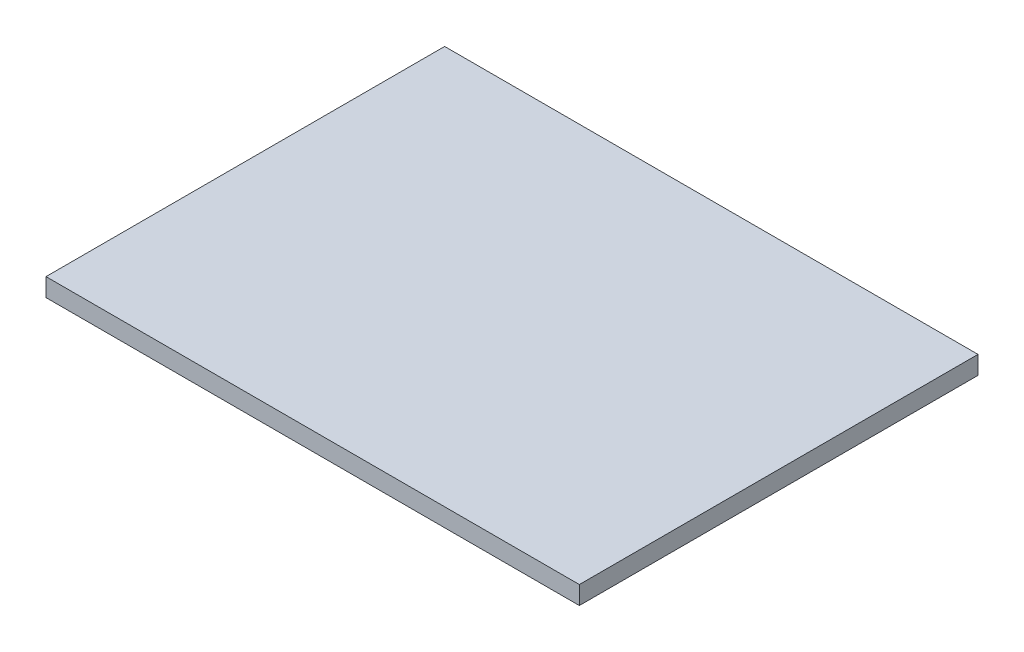
SolidWorks part; units mm, degrees
ref_plane "Płaszczyzna przednia" through (0, 0, 0) normal (0, 0, 1) x (1, 0, 0)
ref_plane "Płaszczyzna górna" through (0, 0, 0) normal (0, 1, 0) x (1, 0, 0)
ref_plane "Płaszczyzna prawa" through (0, 0, 0) normal (1, 0, 0) x (0, 0, -1)
sketch "Szkic1" plane through (0, 0, 0) normal (0, 1, 0) x (1, 0, 0)
  line L1 (-146.5, -109.5) -> (146.5, -109.5)
  line L2 (-146.5, -109.5) -> (-146.5, 109.5)
  line L3 (-146.5, 109.5) -> (146.5, 109.5)
  line L4 (146.5, -109.5) -> (146.5, 109.5)
  line L5 (-146.5, -109.5) -> (146.5, 109.5) construction
  line L6 (-146.5, 109.5) -> (146.5, -109.5) construction
  point P0 (0, 0)
  dimension "D1" = 219
  dimension "D2" = 293
extrude "Dodanie-wyciągnięcie1" add sketch "Szkic1" along normal blind 10
